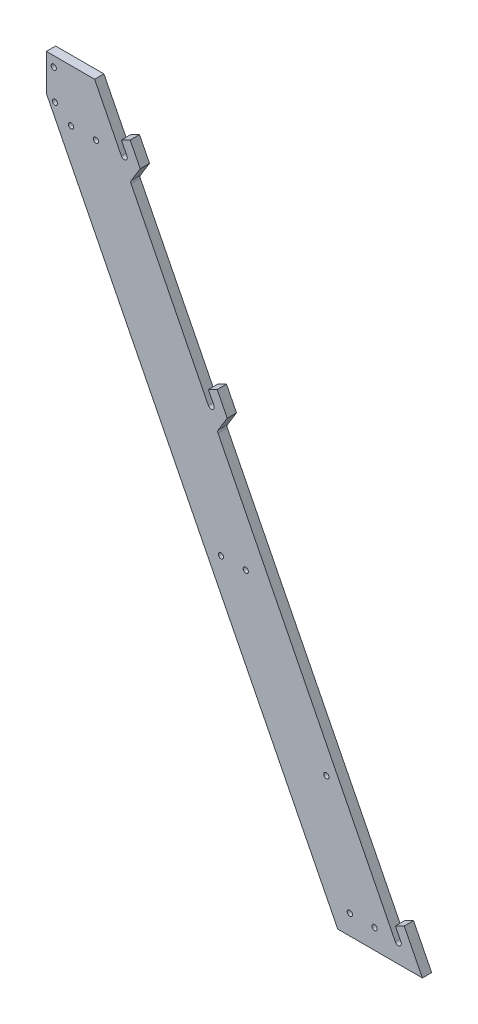
SolidWorks part; units mm, degrees
material "Pine"
ref_plane "Front Plane" through (0, 0, 0) normal (0, 0, 1) x (1, 0, 0)
ref_plane "Top Plane" through (0, 0, 0) normal (0, 1, 0) x (1, 0, 0)
ref_plane "Right Plane" through (0, 0, 0) normal (1, 0, 0) x (0, 0, -1)
sketch "Sketch1" plane through (0, 0, 0) normal (0, 0, 1) x (1, 0, 0)
  line L1 (0, 0) -> (-396.875, 787.4)
  line L4 (0, 0) -> (-85.332, 0)
  line L5 (-396.875, 787.4) -> (-482.207, 787.4)
  line L6 (-482.207, 787.4) -> (-85.332, 0)
  line L7 (215.9, 0) -> (215.9, 787.4) construction
  dimension "D1" = 76.2
  dimension "D2" = 787.4
  dimension "D3" = 215.9
  dimension "D4" = 612.775
extrude "Boss-Extrude1" add sketch "Sketch1" along normal mid plane 11.9062
sketch "Sketch3" plane through (0, 0, 5.9531) normal (0, 0, 1) x (1, 0, 0)
  line L0 (-85.332, 0) -> (0, 0) construction
  line L5 (-396.875, 787.4) -> (-482.207, 787.4) construction
  line L10 (-228.6, 364.871) -> (-275.832, 364.871)
  line L11 (-228.6, 364.871) -> (-228.6, 377.952)
  line L12 (-228.6, 377.952) -> (-275.832, 377.952)
  line L13 (-275.832, 364.871) -> (-275.832, 377.952)
  line L14 (215.9, 0) -> (215.9, 787.4) construction
  line L15 (-273.05, 453.0598) -> (-320.282, 453.0598) construction
  line L16 (-273.05, 453.0598) -> (-273.05, 466.1408) construction
  line L17 (-273.05, 466.1408) -> (-320.282, 466.1408) construction
  line L18 (-320.282, 453.0598) -> (-320.282, 466.1408) construction
  line L19 (-420.6875, 745.9726) -> (-467.9195, 745.9726)
  line L20 (-420.6875, 745.9726) -> (-420.6875, 759.0536)
  line L21 (-420.6875, 759.0536) -> (-467.9195, 759.0536)
  line L22 (-467.9195, 745.9726) -> (-467.9195, 759.0536)
  line L25 (-482.207, 787.4) -> (-85.332, 0) construction
  line L27 (-420.6875, 759.0536) -> (-382.5875, 759.0536) construction
  line L28 (0, 0) -> (-396.875, 787.4) construction
  line L29 (-187.325, 282.9814) -> (-234.557, 282.9814) construction
  line L30 (-187.325, 282.9814) -> (-187.325, 296.0624) construction
  line L31 (-187.325, 296.0624) -> (-234.557, 296.0624) construction
  line L32 (-234.557, 282.9814) -> (-234.557, 296.0624) construction
  line L33 (-495.3, 894.0038) -> (-542.532, 894.0038) construction
  line L34 (-495.3, 894.0038) -> (-495.3, 907.0848) construction
  line L35 (-495.3, 907.0848) -> (-542.532, 907.0848) construction
  line L36 (-542.532, 894.0038) -> (-542.532, 907.0848) construction
  line L37 (-482.207, 787.4) -> (-85.332, 0) construction
  line L38 (-228.6, 364.871) -> (-183.9068, 364.871) construction
  line L39 (0, 0) -> (-396.875, 787.4) construction
  line L40 (-420.6875, 745.9726) -> (-375.9943, 745.9726) construction
  point P5 (-296.666, 466.1408)
  point P36 (-458.7875, 759.0536)
  dimension "D2" = 13.081
  dimension "D3" = 28.3464
  dimension "D4" = 612.775
  dimension "D5" = 76.2
  dimension "D6" = 466.1408
  dimension "D7" = 745.9726
  dimension "D8" = 636.5875
  dimension "D9" = 38.1
  dimension "D10" = 488.95
  dimension "D11" = 444.5
  dimension "D12" = 711.2
  dimension "D13" = 377.952
  dimension "D14" = 81.8896
  dimension "D15" = 403.225
  dimension "D16" = 408.5983
  dimension "D17" = 835.3723
extrude "Cut-Extrude1" cut sketch "Sketch3" against normal through all
sketch "Sketch10" plane through (0, 0, 5.9531) normal (0, 0, 1) x (1, 0, 0)
  line L0 (0, 0) -> (-396.875, 787.4) construction
  line L1 (-244.0247, 501.7803) -> (-249.7409, 513.1212)
  line L2 (-244.0247, 501.7803) -> (-251.1127, 498.2077) construction
  line L3 (-249.7409, 513.1212) -> (-238.4, 518.8373) construction
  line L4 (-238.4, 518.8373) -> (-226.9677, 496.1556)
  line L6 (-239.6804, 475.5259) -> (-251.1127, 498.2077)
  line L7 (0, 0) -> (-396.875, 787.4) construction
  line L8 (-226.9677, 496.1556) -> (-239.6804, 475.5259)
  line L9 (-482.207, 496.1556) -> (0, 496.1556) construction
  line L10 (-396.875, 787.4) -> (-482.207, 787.4) construction
  line L11 (-244.0247, 501.7803) -> (-232.6838, 507.4965) construction
  line L12 (-351.1457, 696.673) -> (-362.578, 719.3548)
  line L13 (-355.49, 722.9274) -> (-361.2061, 734.2682)
  line L14 (-349.8652, 739.9844) -> (-338.4329, 717.3026)
  line L15 (-338.4329, 717.3026) -> (-351.1457, 696.673)
  line L16 (0, 0) -> (-11.4323, 22.6817)
  line L17 (-4.3443, 26.2544) -> (-10.0605, 37.5952)
  line L18 (1.2804, 43.3114) -> (12.7128, 20.6296)
  line L19 (12.7128, 20.6296) -> (0, 0) construction
  line L20 (0, 0) -> (23.1108, 0)
  line L21 (23.1108, 0) -> (12.7128, 20.6296)
  line L22 (-358.3938, 742.7968) -> (-338.3872, 703.1037) construction
  line L23 (-338.3872, 703.1037) -> (-351.1457, 696.673) construction
  line L24 (-355.49, 722.9274) -> (-349.8195, 725.7854) construction
  arc A0 (-244.0247, 501.7803) -> (-251.1127, 498.2077) centre (-247.5687, 499.994) cw
  arc A1 (-249.7409, 513.1212) -> (-238.4, 518.8373) centre (-244.0704, 515.9793) cw
  arc A2 (-355.49, 722.9274) -> (-362.578, 719.3548) centre (-359.034, 721.1411) cw
  arc A3 (-361.2061, 734.2682) -> (-349.8652, 739.9844) centre (-355.5357, 737.1263) cw
  arc A4 (-4.3443, 26.2544) -> (-11.4323, 22.6817) centre (-7.8883, 24.4681) cw
  arc A5 (-10.0605, 37.5952) -> (1.2804, 43.3114) centre (-4.39, 40.4533) cw
  dimension "D1" = 7.9375
  dimension "D2" = 25.4
  dimension "D3" = 12.7
  dimension "D4" = 12.7
  dimension "D5" = 12.7
  dimension "D6" = 291.2444
  dimension "D9" = 101.6
  dimension "D10" = 349.25
  dimension "D11" = 44.45
  dimension "D12" = 19.05
  dimension "D7" = 2
  dimension "D8" = 2
extrude "Boss-Extrude3" add sketch "Sketch10" against normal up to surface (11.9063 mm away) up to face at (-311.4421, 505.8749, -5.9531)
hole_wizard "1/4 Clearance Hole1" positions "Sketch11" profile "Sketch12" hole size "1/4" standard "ANSI Inch" end condition through all
sketch "Sketch11" plane through (0, 0, 5.9531) normal (0, 0, 1) x (1, 0, 0)
  line L0 (-411.0511, 780.2548) -> (-14.1761, -7.1452) construction
  line L4 (0, 0) -> (-14.1761, -7.1452)
  line L6 (-396.875, 787.4) -> (-411.0511, 780.2548)
  line L7 (-251.1127, 498.2077) -> (-351.1457, 696.673) construction
  line L8 (-427.0375, 720.5726) -> (-395.2875, 720.5726) construction
  line L10 (-420.6875, 745.9726) -> (-420.6875, 759.0536) construction
  line L11 (-461.3263, 745.9726) -> (-420.6875, 745.9726) construction
  line L12 (-420.6875, 745.9726) -> (-395.2875, 720.5726) construction
  line L13 (-395.2875, 720.5726) -> (-203.2, 339.471) construction
  line L14 (-228.6, 364.871) -> (-203.2, 339.471) construction
  line L15 (-203.2, 339.471) -> (-234.95, 339.471) construction
  line L16 (-69.85, 25.4) -> (-38.1, 25.4) construction
  line L18 (-85.332, 0) -> (23.1108, 0) construction
  line L19 (215.9, 0) -> (215.9, 787.4) construction
  point P4 (-99.9186, 162.9679)
  point P31 (-427.0375, 720.5726)
  point P40 (-395.2875, 720.5726)
  point P64 (-203.2, 339.471)
  point P67 (-234.95, 339.471)
  point P69 (-69.85, 25.4)
  point P71 (-38.1, 25.4)
  dimension "D1" = 25.4
  dimension "D2" = 15.875
  dimension "D4" = 190.5
  dimension "D5" = 25.4
  dimension "D6" = 31.75
  dimension "D7" = 254
  dimension "D8" = 25.4
sketch "Sketch12" plane through (-99.9186, 162.9679, 5.9531) normal (1, 0, 0) x (0, -1, 0)
  line L0 (0, 0) -> (0, 11.9062)
  line L1 (0, 11.9062) -> (3.3782, 11.9062)
  line L2 (3.3782, 11.9062) -> (3.3782, 0)
  line L5 (3.3782, 0) -> (0, 0)
  line L11 (0, -6.35) -> (0, 107.95) construction
  dimension "Thru Hole Dia." = 6.7564
  dimension "Thru Hole Depth" = 11.9062
sketch "Sketch13" plane through (0, 0, 5.9531) normal (0, 0, 1) x (1, 0, 0)
  line L0 (-420.6875, 745.9726) -> (-420.6875, 759.0536) construction
  line L1 (-458.7875, 759.0536) -> (-482.207, 759.0536)
  line L2 (-458.7875, 759.0536) -> (-458.7875, 787.4)
  line L3 (-458.7875, 787.4) -> (-482.207, 787.4)
  line L4 (-482.207, 759.0536) -> (-482.207, 787.4)
  line L5 (-420.6875, 759.0536) -> (-467.9195, 759.0536) construction
  dimension "D1" = 38.1
extrude "Cut-Extrude2" cut sketch "Sketch13" against normal through all
sketch "Sketch14" plane through (0, 0, 5.9531) normal (0, 0, 1) x (1, 0, 0)
  line L0 (-420.6875, 759.0536) -> (-458.7875, 759.0536) construction
  line L1 (-461.3263, 745.9726) -> (-420.6875, 745.9726) construction
  line L2 (-228.6, 377.952) -> (-275.832, 377.952) construction
  line L3 (-269.2388, 364.871) -> (-228.6, 364.871) construction
  circle A0 centre (-424.1165, 759.0536) radius 3.429
  circle A1 centre (-424.1165, 745.9726) radius 3.429
  circle A2 centre (-232.029, 377.952) radius 3.429
  circle A3 centre (-232.029, 364.871) radius 3.429
  dimension "D1" = 6.858
extrude "Cut-Extrude3" cut sketch "Sketch14" against normal through all
sketch "Sketch15" plane through (0, 0, 5.9531) normal (0, 0, 1) x (1, 0, 0)
  line L0 (-458.7875, 759.0536) -> (-458.7875, 787.4) construction
  line L3 (-396.875, 787.4) -> (-458.7875, 787.4) construction
  point P2 (-447.675, 736.6)
  point P5 (-449.2625, 774.7)
  dimension "D1" = 12.7
  dimension "D2" = 38.1
  dimension "D3" = 11.1125
  dimension "D4" = 9.525
hole_wizard "1/4 Clearance Hole2" positions "Sketch16" profile "Sketch17" hole size "1/4" standard "ANSI Inch" end condition through all
sketch "Sketch16" plane through (0, 0, 5.9531) normal (0, 0, 1) x (1, 0, 0)
  point P8 (-447.675, 736.6)
  point P10 (-449.2625, 774.7)
sketch "Sketch17" plane through (-447.675, 736.6, 5.9531) normal (1, 0, 0) x (0, -1, 0)
  line L0 (0, 0) -> (0, 11.9062)
  line L1 (0, 11.9062) -> (3.3782, 11.9062)
  line L2 (3.3782, 11.9062) -> (3.3782, 0)
  line L5 (3.3782, 0) -> (0, 0)
  line L11 (0, -6.35) -> (0, 107.95) construction
  dimension "Thru Hole Dia." = 6.7564
  dimension "Thru Hole Depth" = 11.9062
sketch "Sketch18" plane through (0, 0, 5.9531) normal (0, 0, 1) x (1, 0, 0)
  line L0 (-458.7875, 745.9726) -> (-458.7875, 740.9356)
  line L1 (-461.3263, 745.9726) -> (-427.5455, 745.9726) construction
  line L2 (-461.3263, 745.9726) -> (-275.832, 377.952) construction
  line L3 (-458.7875, 740.9356) -> (-461.3263, 745.9726)
  line L4 (-461.3263, 745.9726) -> (-458.7875, 745.9726)
  line L5 (-458.7875, 759.0536) -> (-458.7875, 787.4) construction
extrude "Cut-Extrude4" cut sketch "Sketch18" against normal through all
sketch "Sketch19" plane through (0, 0, -5.9531) normal (0, 0, -1) x (-1, 0, 0)
  line L0 (458.7875, 759.0536) -> (458.7875, 745.9726)
  line L1 (458.7875, 745.9726) -> (427.5455, 745.9726) construction
  line L2 (420.6875, 745.9726) -> (420.6875, 759.0536) construction
  line L3 (427.5455, 759.0536) -> (458.7875, 759.0536) construction
  line L4 (458.7875, 745.9726) -> (427.5455, 745.9726)
  line L5 (420.6875, 745.9726) -> (420.6875, 759.0536)
  line L6 (427.5455, 759.0536) -> (458.7875, 759.0536)
  line L7 (269.2388, 364.871) -> (275.832, 377.952)
  line L8 (269.2388, 364.871) -> (235.458, 364.871) construction
  line L9 (228.6, 364.871) -> (228.6, 377.952) construction
  line L10 (235.458, 377.952) -> (275.832, 377.952) construction
  line L11 (269.2388, 364.871) -> (235.458, 364.871)
  line L12 (228.6, 364.871) -> (228.6, 377.952)
  line L13 (235.458, 377.952) -> (275.832, 377.952)
  arc A0 (420.6875, 745.9726) -> (427.5455, 745.9726) centre (424.1165, 745.9726) ccw construction
  arc A1 (427.5455, 759.0536) -> (420.6875, 759.0536) centre (424.1165, 759.0536) ccw construction
  arc A2 (420.6875, 745.9726) -> (427.5455, 745.9726) centre (424.1165, 745.9726) ccw
  arc A3 (427.5455, 759.0536) -> (420.6875, 759.0536) centre (424.1165, 759.0536) ccw
  arc A4 (228.6, 364.871) -> (235.458, 364.871) centre (232.029, 364.871) ccw construction
  arc A5 (235.458, 377.952) -> (228.6, 377.952) centre (232.029, 377.952) ccw construction
  arc A6 (228.6, 364.871) -> (235.458, 364.871) centre (232.029, 364.871) ccw
  arc A7 (235.458, 377.952) -> (228.6, 377.952) centre (232.029, 377.952) ccw
extrude "Boss-Extrude4" add sketch "Sketch19" against normal up to surface (11.9063 mm away) up to face at (-274.555, 500.8983, 5.9531)
sketch "Sketch20" plane through (0, 0, -5.9531) normal (0, 0, -1) x (-1, 0, 0)
  line L0 (349.8652, 739.9844) -> (361.2061, 734.2682)
  line L1 (349.8652, 739.9844) -> (352.7233, 745.6548)
  line L2 (361.2061, 734.2682) -> (364.0642, 739.9387)
  line L3 (352.7233, 745.6548) -> (364.0642, 739.9387)
  line L4 (238.4, 518.8373) -> (249.7409, 513.1212)
  line L5 (238.4, 518.8373) -> (241.2581, 524.5078)
  line L6 (249.7409, 513.1212) -> (252.599, 518.7916)
  line L7 (241.2581, 524.5078) -> (252.599, 518.7916)
  line L8 (-1.2804, 43.3114) -> (10.0605, 37.5952)
  line L9 (-1.2804, 43.3114) -> (1.5777, 48.9818)
  line L10 (10.0605, 37.5952) -> (12.9185, 43.2657)
  line L11 (1.5777, 48.9818) -> (12.9185, 43.2657)
  arc A0 (361.2061, 734.2682) -> (349.8652, 739.9844) centre (355.5357, 737.1263) ccw construction
  arc A1 (249.7409, 513.1212) -> (238.4, 518.8373) centre (244.0704, 515.9793) ccw construction
  arc A2 (10.0605, 37.5952) -> (-1.2804, 43.3114) centre (4.39, 40.4533) ccw construction
extrude "Boss-Extrude5" add sketch "Sketch20" against normal up to surface (11.9062 mm away) up to face at (-236.8137, 466.0046, 5.9531)
sketch "Sketch21" plane through (0, 0, -5.9531) normal (0, 0, -1) x (-1, 0, 0)
  line L0 (352.7233, 745.6548) -> (364.0642, 739.9387)
  line L1 (352.7233, 745.6548) -> (351.2943, 742.8196)
  line L2 (364.0642, 739.9387) -> (362.6352, 737.1034)
  line L3 (351.2943, 742.8196) -> (362.6352, 737.1034)
  line L4 (355.49, 722.9274) -> (364.0642, 739.9387) construction
  line L5 (241.2581, 524.5078) -> (252.599, 518.7916)
  line L6 (241.2581, 524.5078) -> (239.829, 521.6726)
  line L7 (252.599, 518.7916) -> (251.1699, 515.9564)
  line L8 (239.829, 521.6726) -> (251.1699, 515.9564)
  line L9 (1.5777, 48.9818) -> (12.9185, 43.2657)
  line L10 (1.5777, 48.9818) -> (0.1486, 46.1466)
  line L11 (12.9185, 43.2657) -> (11.4895, 40.4304)
  line L12 (0.1486, 46.1466) -> (11.4895, 40.4304)
  dimension "D1" = 3.175
  dimension "D2" = 3.175
  dimension "D3" = 3.175
extrude "Cut-Extrude5" cut sketch "Sketch21" against normal through all
fillet "Fillet1" radius 3.3782 2 edges at (-239.6804, 475.5259, 0) (-351.1457, 696.673, 0)
